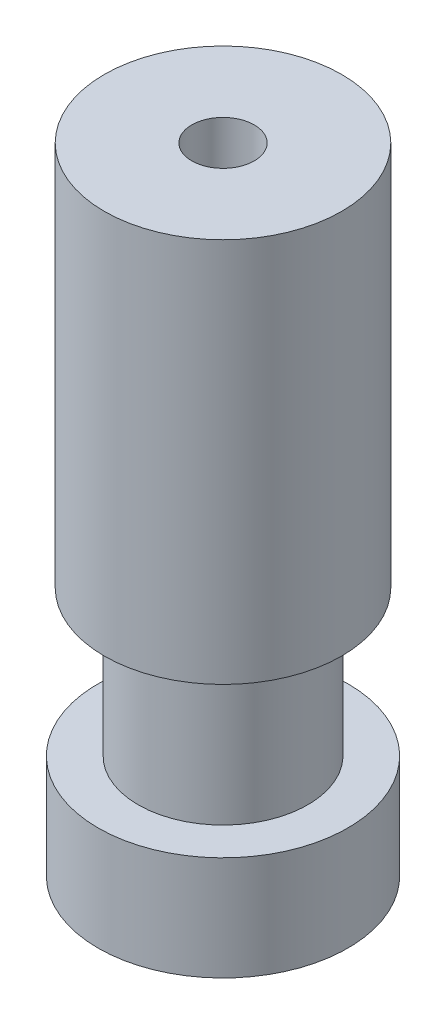
SolidWorks part; units mm, degrees
ref_plane "Front Plane" through (0, 0, 0) normal (0, 0, 1) x (1, 0, 0)
ref_plane "Top Plane" through (0, 0, 0) normal (0, 1, 0) x (1, 0, 0)
ref_plane "Right Plane" through (0, 0, 0) normal (1, 0, 0) x (0, 0, -1)
sketch "Sketch1" plane through (0, 0, 0) normal (0, 1, 0) x (1, 0, 0)
  circle A0 centre (0, 0) radius 6
  dimension "D1" = 12
extrude "Boss-Extrude1" add sketch "Sketch1" along normal blind 5
sketch "Sketch2" plane through (0, 0, 0) normal (0, -1, 0) x (1, 0, 0)
  line L1 (3.2332, 0) -> (1.6166, 2.8)
  line L2 (1.6166, 2.8) -> (-1.6166, 2.8)
  line L3 (-1.6166, 2.8) -> (-3.2332, 0)
  line L4 (-3.2332, 0) -> (-1.6166, -2.8)
  line L5 (-1.6166, -2.8) -> (1.6166, -2.8)
  line L6 (1.6166, -2.8) -> (3.2332, 0)
  circle A0 centre (0, 0) radius 2.8 construction
  dimension "D1" = 5.6
extrude "Cut-Extrude1" cut sketch "Sketch2" against normal blind 3
sketch "Sketch3" plane through (0, 5, 0) normal (0, 1, 0) x (1, 0, 0)
  circle A0 centre (0, 0) radius 4.075
  dimension "D1" = 8.15
extrude "Boss-Extrude2" add sketch "Sketch3" along normal blind 7
sketch "Sketch4" plane through (0, 12, 0) normal (0, 1, 0) x (1, 0, 0)
  circle A0 centre (0, 0) radius 5.7
  dimension "D1" = 11.4
extrude "Boss-Extrude3" add sketch "Sketch4" along normal blind 18.5
hole_wizard "Ø1.0mm Dowel Hole1" positions "Sketch5" profile "Sketch6" hole size "Ø1.0" standard "ANSI Metric"
sketch "Sketch5" plane through (0, 30.5, 0) normal (0, 1, 0) x (1, 0, 0)
  point P0 (0, 0)
sketch "Sketch6" plane through (0, 30.5, 0) normal (1, 0, 0) x (0, 0, 1)
  line L0 (0, 0) -> (0, 31.4013)
  line L1 (0, 31.4013) -> (1.5, 30.5)
  line L2 (1.5, 30.5) -> (1.5, 0)
  line L5 (1.5, 0) -> (0, 0)
  line L10 (0, 31.4013) -> (-1.5, 30.5) construction
  line L11 (0, -6.35) -> (0, 107.95) construction
  dimension "Hole Dia." = 3
  dimension "Hole Depth" = 30.5
  dimension "Drill Angle" = 118
